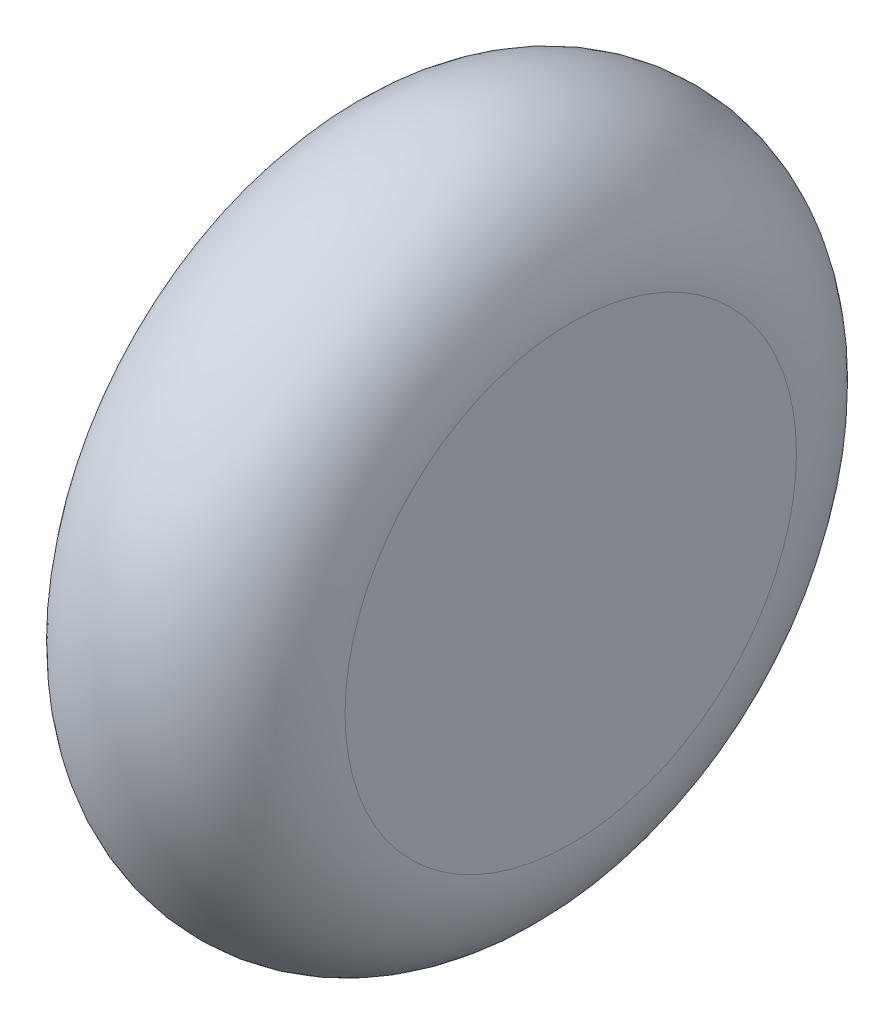
SolidWorks part; units mm, degrees
ref_plane "Front Plane" through (0, 0, 0) normal (0, 0, 1) x (1, 0, 0)
ref_plane "Top Plane" through (0, 0, 0) normal (0, 1, 0) x (1, 0, 0)
ref_plane "Right Plane" through (0, 0, 0) normal (1, 0, 0) x (0, 0, -1)
sketch "Sketch1" plane through (0, 0, 0) normal (0, 1, 0) x (1, 0, 0)
  line L0 (-123.825, 0) -> (140.0969, 0) construction
  line L1 (-25.4, 0) -> (-25.4, 46.355)
  line L2 (25.4, 0) -> (25.4, 46.355)
  line L3 (-25.4, 0) -> (25.4, 0)
  arc A0 (-25.4, 46.355) -> (25.4, 46.355) centre (0, 46.355) cw
  dimension "D3" = 46.355
  dimension "D1" = 25.4
  dimension "D2" = 25.4
revolve "Revolve1" add sketch "Sketch1" angle 360 about L0
